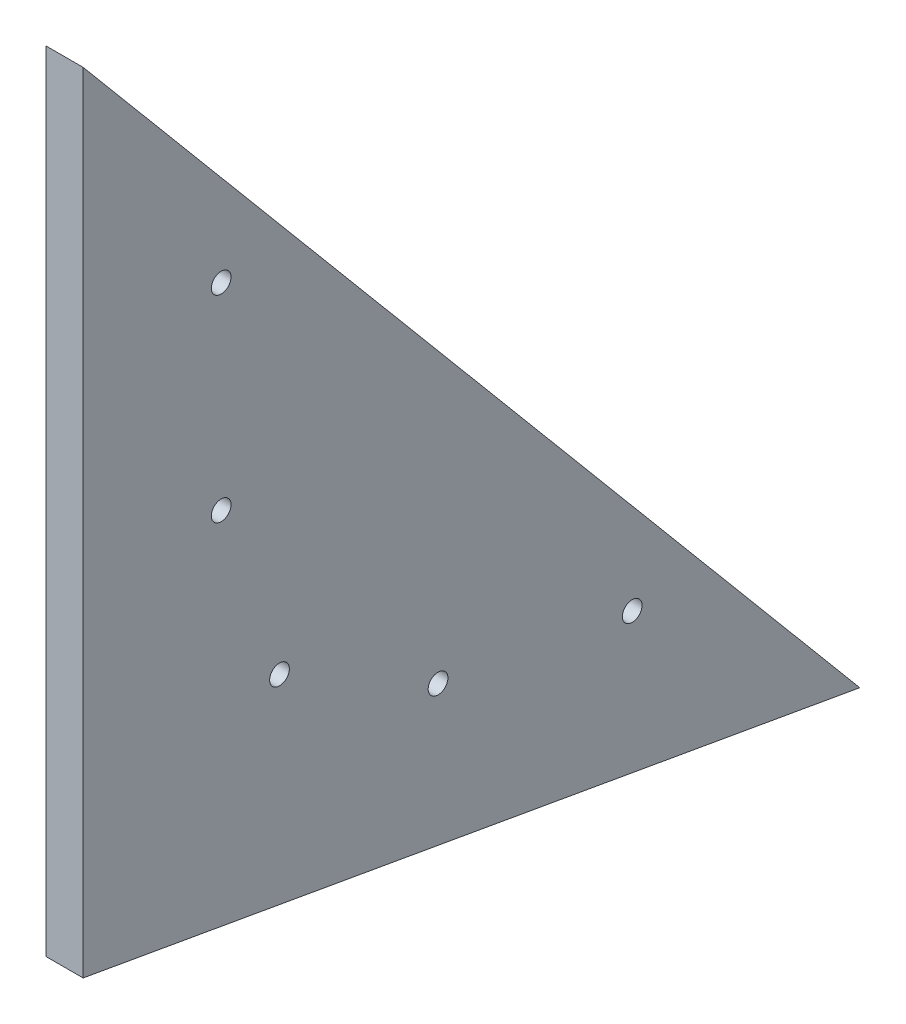
SolidWorks part; units mm, degrees
ref_plane "Front" through (0, 0, 0) normal (0, 0, 1) x (1, 0, 0)
ref_plane "Top" through (0, 0, 0) normal (0, 1, 0) x (1, 0, 0)
ref_plane "Right" through (0, 0, 0) normal (1, 0, 0) x (0, 0, -1)
sketch "Sketch1" plane through (0, 0, 0) normal (1, 0, 0) x (0, 0, -1)
  line L0 (0, 0) -> (0, 254)
  line L1 (0, 254) -> (250.1412, -44.1066)
  line L3 (0, 0) -> (250.1412, -44.1066)
  dimension "D1" = 254
  dimension "D2" = 100
extrude "Boss-Extrude1" add sketch "Sketch1" along normal blind 11.9062
hole_wizard "1/4 (0.25) Diameter Hole1" positions "Sketch2" profile "Sketch3" hole size "1/4" standard "ANSI Inch" end condition through all
sketch "Sketch2" plane through (0, 0, 0) normal (-1, 0, 0) x (0, 0, 1)
  line L0 (0, 0) -> (-125.0706, 104.9467) construction
  line L1 (-250.1412, -44.1066) -> (0, 254) construction
  line L2 (0, 254) -> (0, 0) construction
  point P0 (-44.45, 171.7255)
  point P3 (-44.45, 108.2255)
  point P6 (-63.237, 53.0621)
  point P31 (-114.3, 24.9815)
  point P32 (-176.8353, 13.9549)
  dimension "D1" = 82.55
  dimension "D2" = 44.45
  dimension "D3" = 44.45
  dimension "D4" = 18.8343
  dimension "D5" = 59.6513
sketch "Sketch3" plane through (0, 171.7255, -44.45) normal (0, 1, 0) x (0, 0, 1)
  line L0 (0, 0) -> (0, 11.9062)
  line L1 (0, 11.9062) -> (3.175, 11.9062)
  line L2 (3.175, 11.9062) -> (3.175, 0)
  line L5 (3.175, 0) -> (0, 0)
  line L11 (0, -6.35) -> (0, 107.95) construction
  dimension "Thru Hole Dia." = 6.35
  dimension "Thru Hole Depth" = 11.9062
